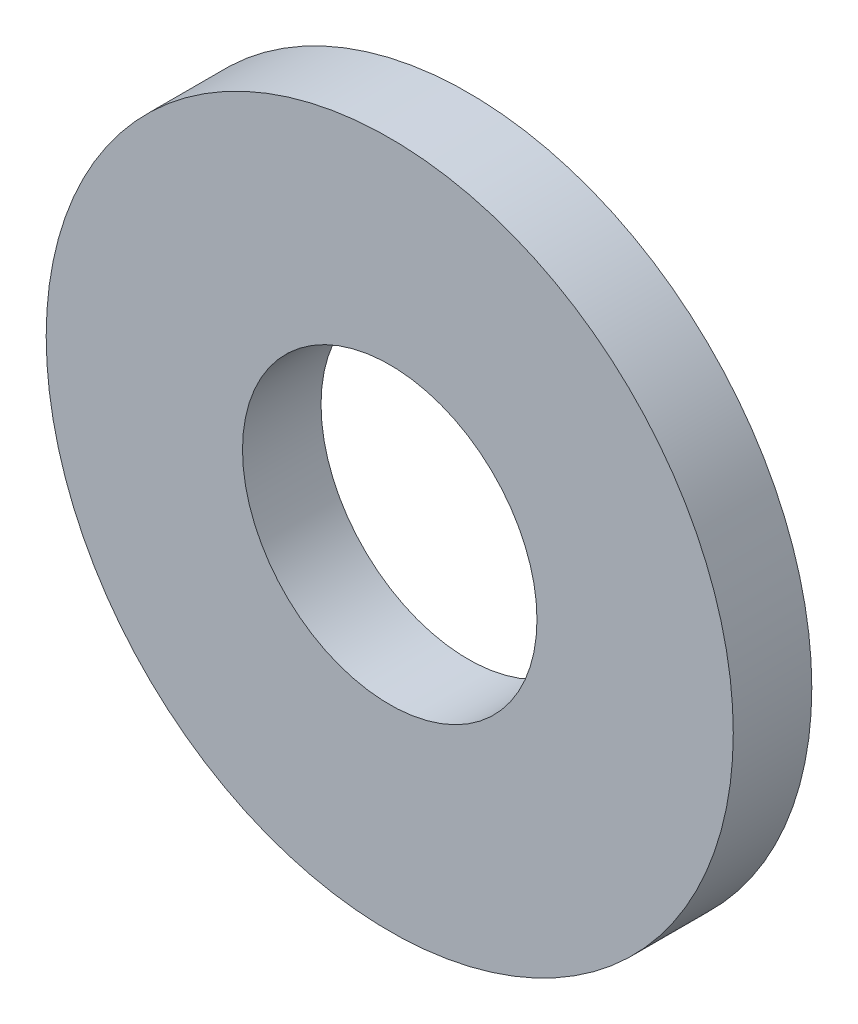
SolidWorks part; units mm, degrees
ref_plane "Front Plane" through (0, 0, 0) normal (0, 0, 1) x (1, 0, 0)
ref_plane "Top Plane" through (0, 0, 0) normal (0, 1, 0) x (1, 0, 0)
ref_plane "Right Plane" through (0, 0, 0) normal (1, 0, 0) x (0, 0, -1)
sketch "Sketch1" plane through (0, 0, 0) normal (1, 0, 0) x (0, 0, -1)
  line L0 (0, -4.7625) -> (0, 4.7625) construction
  line L1 (0, -11.1125) -> (0, 11.1125) construction
  line L2 (-1.27, 11.1125) -> (1.27, 11.1125)
  point P4 (0, 0)
  point P8 (0, 0)
  point P10 (0, 11.1125)
  dimension "Thickness" = 2.54
sketch "Sketch2" plane through (0, 0, 0) normal (0, 0, 1) x (1, 0, 0)
  line L1 (0, -4.7625) -> (0, 4.7625) construction
  circle A2 centre (0, 0) radius 4.7625
  circle A3 centre (0, 0) radius 11.1125
  point P3 (0, 0)
  dimension "D1" = 9.525
  dimension "D2" = 22.225
extrude "Boss-Extrude1" add sketch "Sketch2" along normal mid plane 2.54
equation "\"D1@Boss-Extrude1\"=\"Thickness@Sketch1\""
equation "\"D1@Sketch2\"=\"ID@Sketch1\""
equation "\"D2@Sketch2\"=\"OD@Sketch1\""
